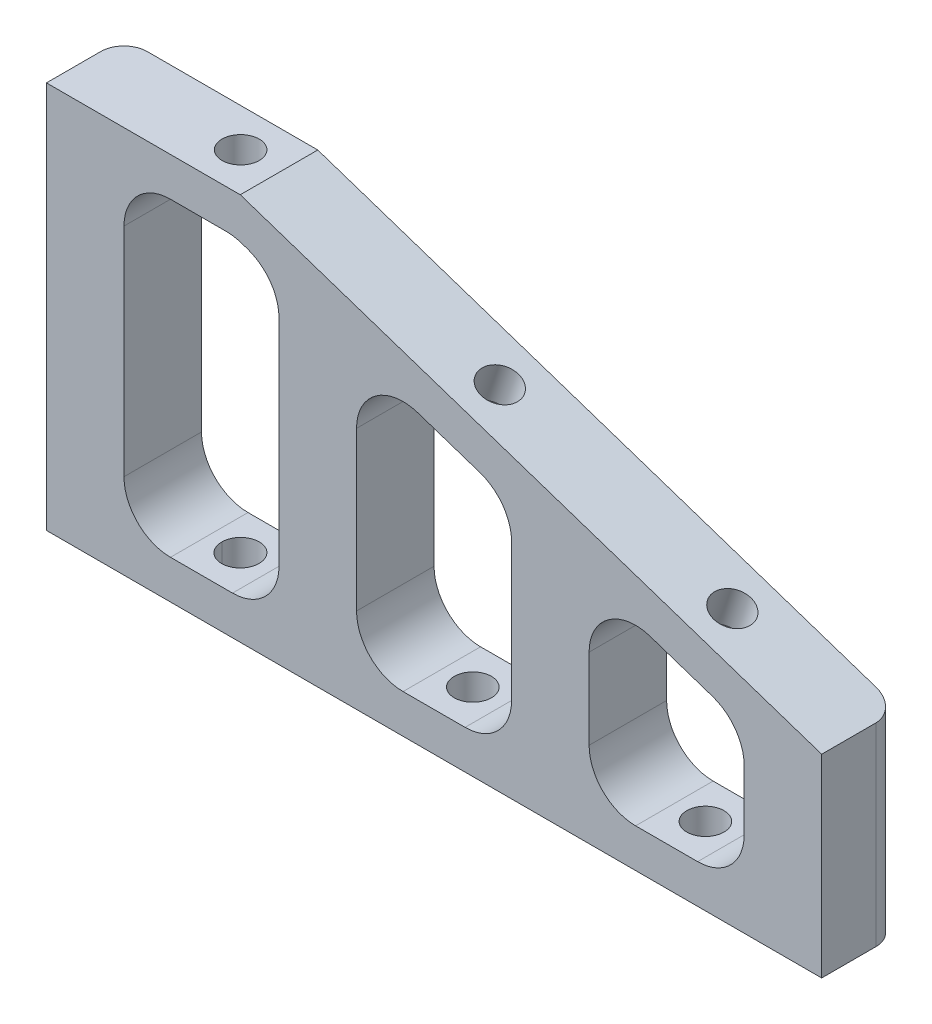
SolidWorks part; units mm, degrees
ref_plane "Plan de face" through (0, 0, 0) normal (0, 0, 1) x (1, 0, 0)
ref_plane "Plan de dessus" through (0, 0, 0) normal (0, 1, 0) x (1, 0, 0)
ref_plane "Plan de droite" through (0, 0, 0) normal (1, 0, 0) x (0, 0, -1)
sketch "Esquisse1" plane through (0, 0, 0) normal (0, 0, 1) x (1, 0, 0)
  line L0 (0, 0) -> (100, 0)
  line L1 (0, 0) -> (0, 25)
  line L2 (100, 0) -> (100, 25)
  line L3 (0, 25) -> (100, 25)
  line L4 (0, 0) -> (0, 50)
  line L5 (0, 0) -> (25, 0)
  line L6 (0, 50) -> (25, 50)
  line L7 (25, 0) -> (25, 50)
  line L8 (25, 50) -> (100, 25)
  line L9 (25, 44.7295) -> (84.1886, 25)
  line L10 (10, 45) -> (30, 45)
  line L11 (10, 45) -> (10, 5)
  line L12 (30, 45) -> (30, 5)
  line L13 (10, 5) -> (30, 5)
  line L14 (40, 5) -> (60, 5)
  line L15 (40, 5) -> (40, 45)
  line L16 (60, 5) -> (60, 45)
  line L17 (40, 45) -> (60, 45)
  line L18 (70, 45) -> (70, 5)
  line L19 (70, 45) -> (90, 45)
  line L20 (70, 5) -> (90, 5)
  line L21 (90, 45) -> (90, 5)
  line L22 (20, 0) -> (20, 45) construction
  line L23 (20, 45) -> (50, 0) construction
  line L24 (50, 0) -> (50, 45) construction
  line L25 (50, 45) -> (80, 0) construction
  line L26 (80, 0) -> (80, 45) construction
  line L27 (84.1886, 25) -> (100, 19.7295)
  line L28 (25, 44.7295) -> (9.1886, 50)
  line L29 (80, 26.3962) -> (81.5811, 31.1396) construction
  line L30 (51.5811, 41.1396) -> (50, 36.3962) construction
  point P29 (50, 45)
  point P31 (80, 45)
  point P32 (50, 0)
  dimension "D1" = 25
  dimension "D2" = 50
  dimension "D3" = 100
  dimension "D4" = 25
  dimension "D5" = 30
  dimension "D6" = 30
  dimension "D7" = 5
  dimension "D8" = 5
  dimension "D9" = 5
  dimension "D10" = 10
  dimension "D11" = 10
  dimension "D12" = 10
  dimension "D13" = 10
extrude "Boss.-Extru.1" add sketch "Esquisse1" along normal blind 10 contours L28 L10 L7 L6 | L9 L15 L8 L7 L10 L12 | L12 L10 L7 L9 | L28 L7 L10 | L10 L28 L6 L4 L3 L11 | L13 L11 L3 L1 L0 L7 | L27 L21 L20 L18 L3 L16 L14 L15 L12 L13 L7 L0 L2 | L3 L15 L9 L12 | L9 L16 L8 L15 | L18 L8 L16 L9 | L18 L9 L16 L3 | L21 L8 L18 L9 L3 | L8 L21 L3 | L21 L27 L2 L3 | L3 L27 L21
fillet "Congé1" radius 6 13 edges at (40, 39.7295, 5) (40, 5, 5) (60, 5, 5) (60, 33.0629, 5) (30, 43.0629, 5) (24.1886, 45, 5) (10, 45, 5) (10, 5, 5) (30, 5, 5) (70, 29.7295, 5) (70, 5, 5) (90, 5, 5) (90, 23.0629, 5)
sketch "Esquisse3" plane through (15.9189, 47.7566, 0) normal (-0.3162, -0.9487, 0) x (0.9487, -0.3162, 0)
  line L0 (33.7083, 10) -> (42.141, 0) construction
  line L1 (42.141, 0) -> (65.3311, 0) construction
  line L2 (65.3311, 0) -> (73.7638, 10) construction
  circle A0 centre (37.9247, 5) radius 2.4
  circle A1 centre (69.5475, 5) radius 2.4
  dimension "D1" = 4.8
  dimension "D2" = 4.8
extrude "Enlèv. mat.-Extru.1" cut sketch "Esquisse3" against normal blind 10
sketch "Esquisse4" plane through (0, 0, 0) normal (0, -1, 0) x (1, 0, 0)
  line L0 (0, 10) -> (100, 0) construction
  line L1 (100, 0) -> (100, 10) construction
  line L2 (100, 10) -> (0, 0) construction
  line L3 (0, 0) -> (0, 5) construction
  line L4 (0, 10) -> (0, 0) construction
  line L5 (0, 5) -> (100, 5) construction
  circle A0 centre (20, 5) radius 2.4
  circle A1 centre (50, 5) radius 2.4
  circle A2 centre (80, 5) radius 2.4
  dimension "D3" = 4.8
  dimension "D4" = 4.8
  dimension "D5" = 4.8
  dimension "D1" = 30
  dimension "D2" = 30
extrude "Enlèv. mat.-Extru.2" cut sketch "Esquisse4" against normal blind 10
sketch "Esquisse5" plane through (0, 50, 0) normal (0, 1, 0) x (1, 0, 0)
  line L0 (0, -5) -> (25, -5) construction
  line L1 (0, -10) -> (0, 0) construction
  line L2 (25, -10) -> (25, 0) construction
  circle A0 centre (20, -4.9507) radius 2.4
  dimension "D1" = 4.8
  dimension "D2" = 20
extrude "Enlèv. mat.-Extru.3" cut sketch "Esquisse5" against normal through all
fillet "Congé2" radius 3 2 edges at (0, 25, 0) (100, 12.5, 0)
